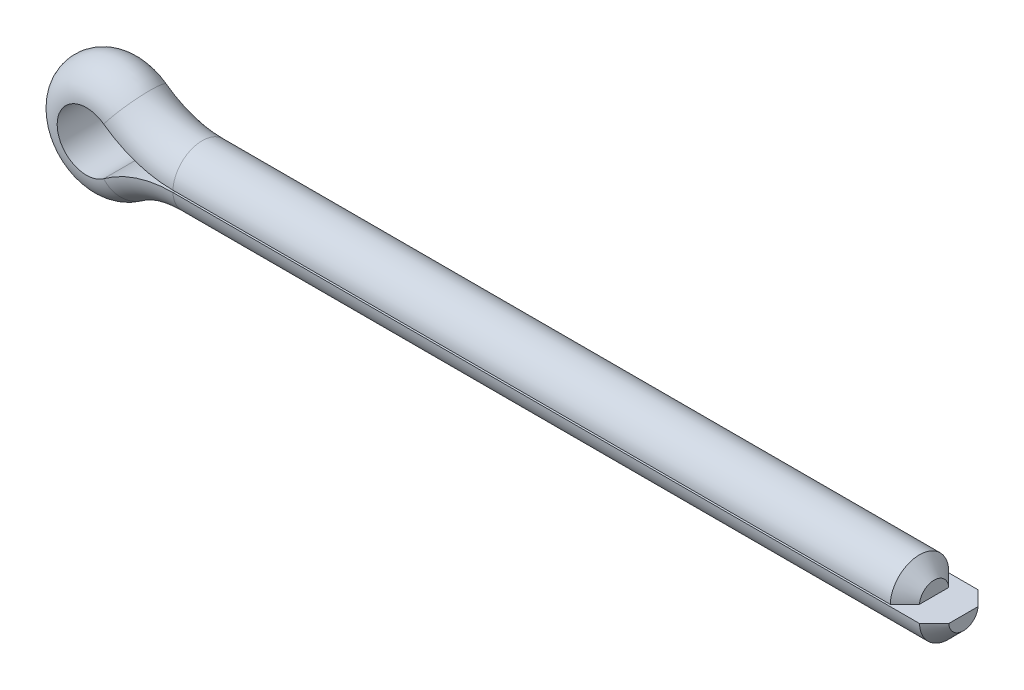
SolidWorks part; units mm, degrees
ref_plane "Front" through (0, 0, 0) normal (0, 0, 1) x (1, 0, 0)
ref_plane "Top" through (0, 0, 0) normal (0, 1, 0) x (1, 0, 0)
ref_plane "Right" through (0, 0, 0) normal (1, 0, 0) x (0, 0, -1)
sketch "Sketch1" plane through (0, 0, 0) normal (0, 0, 1) x (1, 0, 0)
  line L0 (-21.3017, 0) -> (0.762, 0) construction
  line L1 (-19.05, -0.0254) -> (0.762, -0.0254)
  line L2 (-20.5402, 0.0254) -> (0.762, 0.0254) construction
  line L3 (-19.05, 0.0254) -> (0, 0.0254)
  line L4 (-11.4985, 0.0254) -> (0.762, 0.0254) construction
  line L5 (-11.4985, -0.0254) -> (0.762, -0.0254) construction
  line L6 (-21.3017, 0.762) -> (-21.3017, 0) construction
  line L7 (-21.3017, 0.762) -> (-21.3017, 1.524) construction
  line L8 (-11.4985, 0) -> (0.762, 0) construction
  line L9 (0, 0.0254) -> (0, 0) construction
  line L10 (-21.3017, 0) -> (-21.3017, -1.524) construction
  line L11 (-19.05, 0.7366) -> (-19.05, -0.7874) construction
  arc A1 (-20.8514, 0.6147) -> (-20.8514, -0.6147) centre (-21.3017, 0) ccw
  arc A2 (-19.05, -0.0254) -> (-20.8514, -0.6147) centre (-19.05, -3.0734) ccw
  arc A3 (-20.8514, 0.6147) -> (-19.05, 0.0254) centre (-19.05, 3.0734) ccw
  circle A4 centre (-21.3017, 0) radius 1.524 construction
  point P15 (0, 0.0254)
  dimension "D6" = 3.048
  dimension "Head Diameter" = 3.048
  dimension "ExtendedProngLength" = 0.762
  dimension "Length" = 19.05
  dimension "Diameter" = 1.524
  dimension "D1" = 0.762
  dimension "D4" = 0.0254
  dimension "D5" = 0.0254
sketch "Sketch2" plane through (0, 0, 0) normal (1, 0, 0) x (0, 0, -1)
  line L0 (-0.7616, 0.0254) -> (0.7616, 0.0254)
  line L1 (0, 0.762) -> (0, -0.762) construction
  circle A1 centre (0, 0) radius 0.762 construction
  arc A2 (-0.7616, 0.0254) -> (0.7616, 0.0254) centre (0, 0) cw
  point P5 (0, 0)
  dimension "D1" = 0.762
sketch "Sketch3" plane through (0, 0, 0) normal (0, 0, 1) x (1, 0, 0)
  line L0 (-19.05, -0.0254) -> (0.762, -0.0254) construction
  line L1 (-19.05, 0.0254) -> (0, 0.0254) construction
  line L2 (-19.05, -0.0254) -> (0.762, -0.0254)
  line L3 (-19.05, 0.0254) -> (0, 0.0254)
  arc A0 (-19.05, -0.0254) -> (-20.8514, -0.6147) centre (-19.05, -3.0734) ccw construction
  arc A1 (-20.8514, 0.6147) -> (-19.05, 0.0254) centre (-19.05, 3.0734) ccw construction
  arc A2 (-20.8514, 0.6147) -> (-20.8514, -0.6147) centre (-21.3017, 0) ccw construction
  arc A3 (-19.05, -0.0254) -> (-20.8514, -0.6147) centre (-19.05, -3.0734) ccw
  arc A4 (-20.8514, 0.6147) -> (-19.05, 0.0254) centre (-19.05, 3.0734) ccw
  arc A5 (-20.8514, 0.6147) -> (-20.8514, -0.6147) centre (-21.3017, 0) ccw
sketch "Sketch4" plane through (0, 0, 0) normal (1, 0, 0) x (0, 0, -1)
  line L0 (-0.7616, 0.0254) -> (0.7616, 0.0254) construction
  line L1 (-0.7616, 0.0254) -> (0.7616, 0.0254)
  arc A2 (0.7616, 0.0254) -> (-0.7616, 0.0254) centre (0, 0) ccw construction
  arc A3 (0.7616, 0.0254) -> (-0.7616, 0.0254) centre (0, 0) ccw
sweep "Sweep1" add profiles "Sketch4" path "Sketch3"
chamfer "Chamfer1" distance 0.381 angle 45 2 edges at (0.762, -0.762, 0) (0, 0.762, 0)
equation "\"D6@Sketch1\"=\"Head Diameter@Sketch1\""
equation "\"D1@Sketch2\"=\"Diameter@Sketch1\"/2"
equation "\"ExtendedProngLength@Sketch1\" = \"Length@Sketch1\"*.09"
equation "\"D1@Chamfer1\"=\"Diameter@Sketch1\"/4"
equation "\"D1@Sketch1\"=\"Diameter@Sketch1\"/2"
